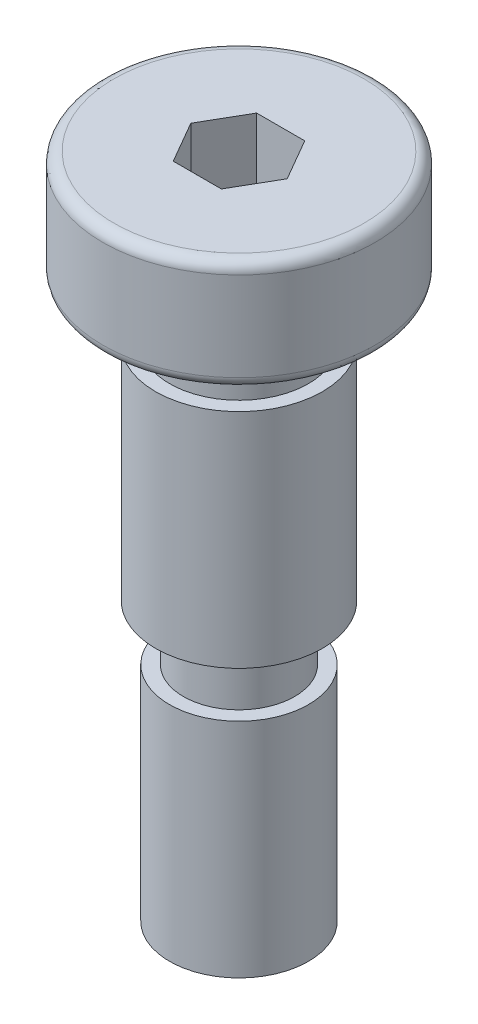
SolidWorks part; units mm, degrees
material "AISI 304"
ref_plane "前视基准面" through (0, 0, 0) normal (0, 0, 1) x (1, 0, 0)
ref_plane "上视基准面" through (0, 0, 0) normal (0, 1, 0) x (1, 0, 0)
ref_plane "右视基准面" through (0, 0, 0) normal (1, 0, 0) x (0, 0, -1)
sketch "草图1" plane through (0, 0, 0) normal (0, 0, 1) x (1, 0, 0)
  line L0 (0, 0) -> (0, 24) construction
  line L1 (0, 24) -> (-4.5, 24)
  line L2 (-4.9, 23.6) -> (-4.9, 20.4)
  line L3 (-4.5, 20) -> (-2.5, 20)
  line L4 (-2.5, 20) -> (-2.5, 18)
  line L5 (-2.5, 18) -> (-3, 18)
  line L6 (-3, 18) -> (-3, 10)
  line L7 (-3, 10) -> (-2, 10)
  line L8 (-2, 10) -> (-2, 8)
  line L9 (-2, 8) -> (-2.5, 8)
  line L10 (-2.5, 8) -> (-2.5, 0)
  line L11 (-2.5, 0) -> (0, 0)
  line L12 (0, 0) -> (0, 24)
  arc A0 (-4.9, 20.4) -> (-4.5, 20) centre (-4.5, 20.4) ccw
  arc A1 (-4.5, 24) -> (-4.9, 23.6) centre (-4.5, 23.6) ccw
  point P17 (-4.9, 20)
  point P20 (-4.9, 24)
  dimension "D11" = 0.4
  dimension "D1" = 4
  dimension "D2" = 9.8
  dimension "D3" = 6
  dimension "D4" = 2
  dimension "D5" = 0.5
  dimension "D6" = 10
  dimension "D7" = 5
  dimension "D8" = 4
  dimension "D9" = 2
  dimension "D10" = 10
revolve "旋转1" add sketch "草图1" angle 360 about L0
cosmetic thread "装饰螺纹线1" parameters "D2"=4.11
sketch "草图2" plane through (0, 24, 0) normal (0, 1, 0) x (1, 0, 0)
  line L1 (0.866, 1.5) -> (-0.866, 1.5)
  line L2 (-0.866, 1.5) -> (-1.7321, 0)
  line L3 (-1.7321, 0) -> (-0.866, -1.5)
  line L4 (-0.866, -1.5) -> (0.866, -1.5)
  line L5 (0.866, -1.5) -> (1.7321, 0)
  line L6 (1.7321, 0) -> (0.866, 1.5)
  circle A0 centre (0, 0) radius 1.5 construction
  dimension "D1" = 3
extrude "切除-拉伸1" cut sketch "草图2" against normal blind 3.5
